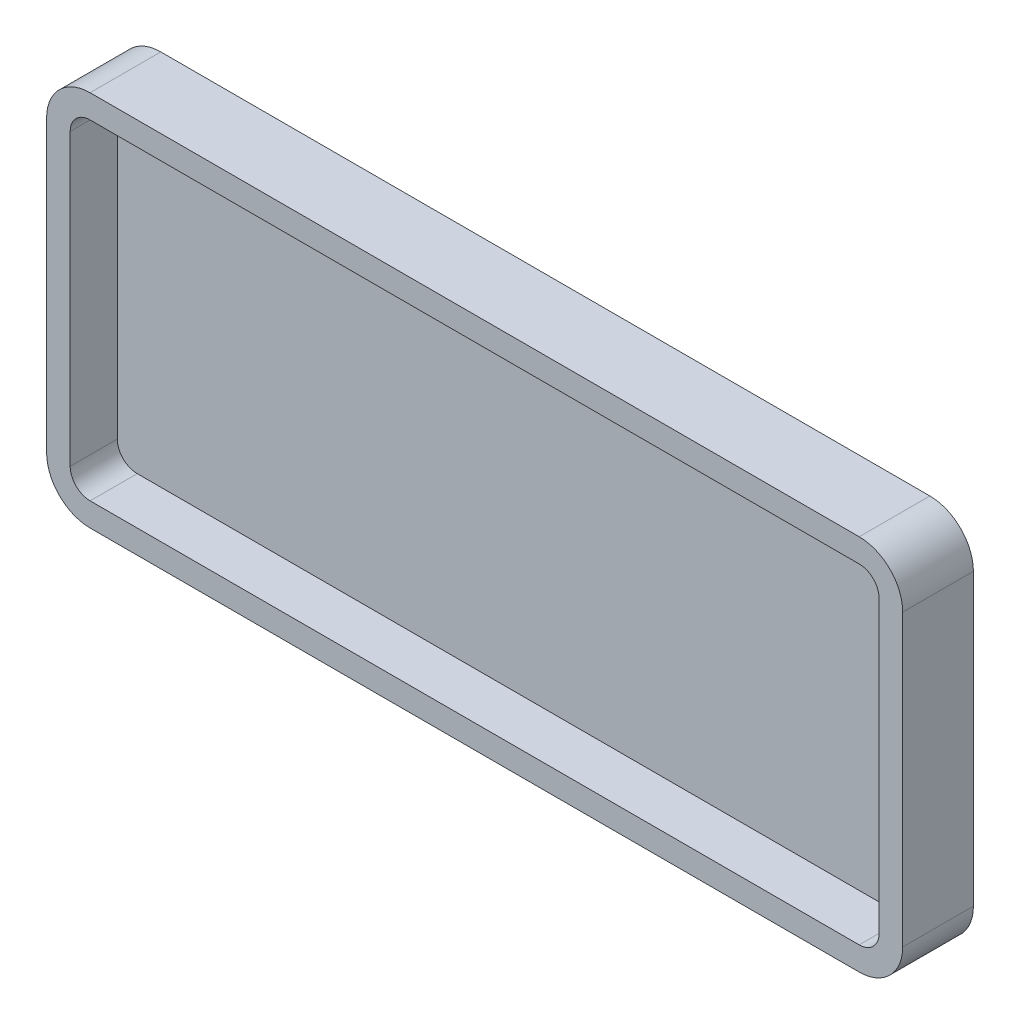
SolidWorks part; units mm, degrees
ref_plane "Plan de face" through (0, 0, 0) normal (0, 0, 1) x (1, 0, 0)
ref_plane "Plan de dessus" through (0, 0, 0) normal (0, 1, 0) x (1, 0, 0)
ref_plane "Plan de droite" through (0, 0, 0) normal (1, 0, 0) x (0, 0, -1)
sketch "Esquisse1" plane through (0, 0, 0) normal (0, 0, 1) x (1, 0, 0)
  line L1 (-24.48, -10.5) -> (24.48, -10.5)
  line L2 (-25.75, -9.23) -> (-25.75, 9.23)
  line L3 (-24.48, 10.5) -> (24.48, 10.5)
  line L4 (25.75, -9.23) -> (25.75, 9.23)
  line L5 (-25.75, -10.5) -> (25.75, 10.5) construction
  line L6 (-25.75, 10.5) -> (25.75, -10.5) construction
  arc A0 (24.48, -10.5) -> (25.75, -9.23) centre (24.48, -9.23) ccw
  arc A1 (-24.48, -10.5) -> (-25.75, -9.23) centre (-24.48, -9.23) cw
  arc A2 (-25.75, 9.23) -> (-24.48, 10.5) centre (-24.48, 9.23) cw
  arc A3 (24.48, 10.5) -> (25.75, 9.23) centre (24.48, 9.23) cw
  point P0 (0, 0)
  dimension "D3" = 1.27
  dimension "D1" = 51.5
  dimension "D2" = 21
extrude "Boss.-Extru.1" add sketch "Esquisse1" along normal blind 3
shell "Coque1" thickness 1.5
ref_plane "PlanMedian" through (0, 0, 0) normal (0, 1, 0) x (1, 0, 0)
ref_plane "PlanSagital" through (0, 0, 0) normal (-1, 0, 0) x (0, 0, 1)
